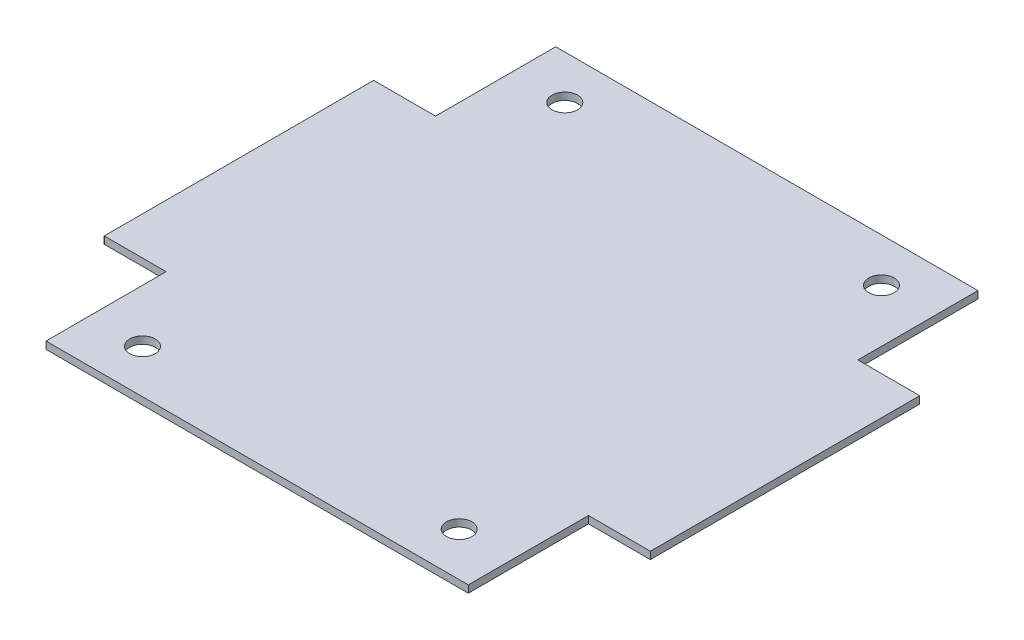
SolidWorks part; units mm, degrees
ref_plane "Front" through (0, 0, 0) normal (0, 0, 1) x (1, 0, 0)
ref_plane "Top" through (0, 0, 0) normal (0, 1, 0) x (1, 0, 0)
ref_plane "Right" through (0, 0, 0) normal (1, 0, 0) x (0, 0, -1)
sketch "Эскиз1" plane through (0, 0, 0) normal (0, 1, 0) x (1, 0, 0)
  line L0 (-37.5, 18.5) -> (-29, 18.5)
  line L1 (-29, 18.5) -> (-29, 35)
  line L2 (-29, 35) -> (29, 35)
  line L3 (29, 35) -> (29, 18.5)
  line L4 (29, 18.5) -> (37.5, 18.5)
  line L5 (37.5, 18.5) -> (37.5, -18.5)
  line L6 (37.5, -18.5) -> (29, -18.5)
  line L7 (29, -18.5) -> (29, -35)
  line L8 (29, -35) -> (-29, -35)
  line L9 (-29, -35) -> (-29, -18.5)
  line L10 (-29, -18.5) -> (-37.5, -18.5)
  line L11 (-37.5, -18.5) -> (-37.5, 18.5)
  point P11 (-37.5, 0)
  point P13 (0, 35)
  dimension "D1" = 75
  dimension "D2" = 70
  dimension "D3" = 37
  dimension "D4" = 58
extrude "Бобышка-Вытянуть1" add sketch "Эскиз1" along normal blind 1
sketch "Эскиз2" plane through (0, 0, 0) normal (0, 1, 0) x (1, 0, 0)
  line L1 (-21.75, 29) -> (21.75, 29) construction
  line L2 (-21.75, 29) -> (-21.75, -29) construction
  line L3 (-21.75, -29) -> (21.75, -29) construction
  line L4 (21.75, 29) -> (21.75, -29) construction
  line L5 (-21.75, 29) -> (21.75, -29) construction
  line L6 (-21.75, -29) -> (21.75, 29) construction
  circle A0 centre (-21.75, 29) radius 1.75
  circle A1 centre (21.75, 29) radius 1.75
  circle A2 centre (21.75, -29) radius 1.75
  circle A3 centre (-21.75, -29) radius 1.75
  point P0 (0, 0)
  dimension "D3" = 3.5
  dimension "D1" = 58
  dimension "D2" = 43.5
extrude "Вырез-Вытянуть1" cut sketch "Эскиз2" along normal blind 1
